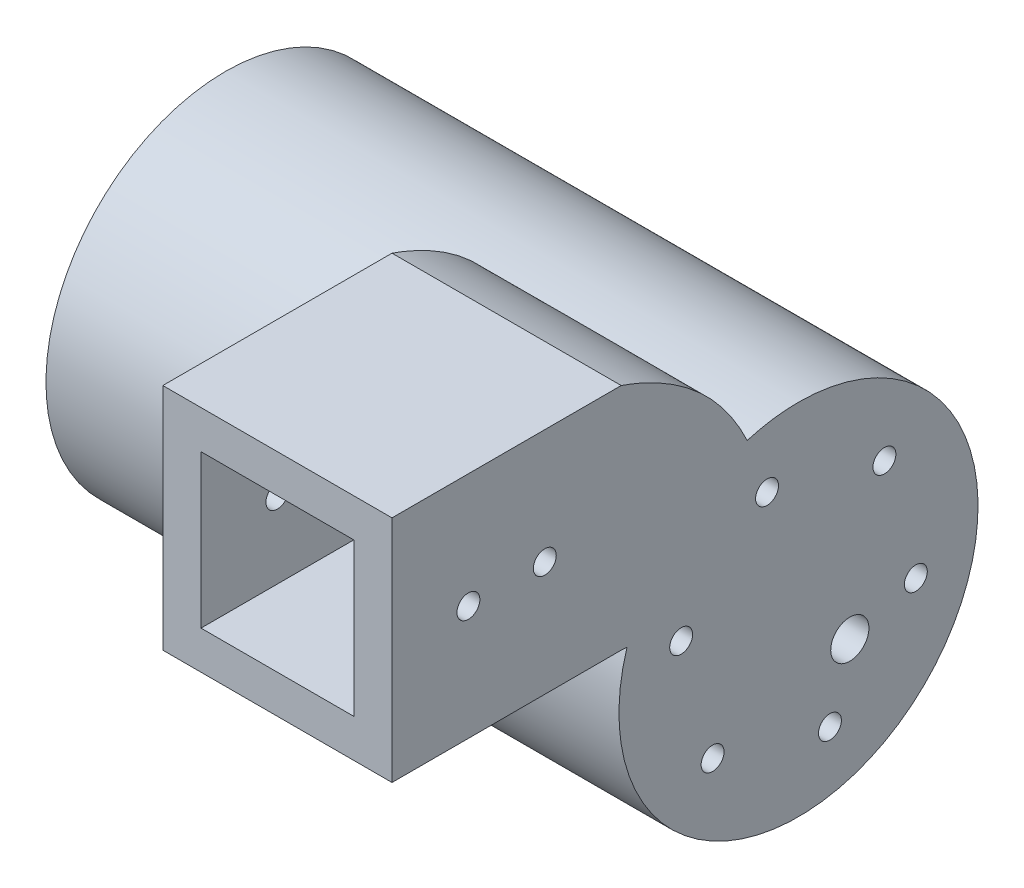
SolidWorks part; units mm, degrees
ref_plane "Front Plane" through (0, 0, 0) normal (0, 0, 1) x (1, 0, 0)
ref_plane "Top Plane" through (0, 0, 0) normal (0, 1, 0) x (1, 0, 0)
ref_plane "Right Plane" through (0, 0, 0) normal (1, 0, 0) x (0, 0, -1)
sketch "Sketch1" plane through (0, 0, 0) normal (0, 0, 1) x (1, 0, 0)
  line L15 (-10, 10) -> (10, 10)
  line L34 (-10, 10) -> (-10, -10)
  line L35 (-10, -10) -> (10, -10)
  line L50 (10, 10) -> (10, -10)
  line L51 (-10, 10) -> (10, -10) construction
  line L66 (-10, -10) -> (10, 10) construction
  line L69 (-15, 15) -> (15, 15)
  line L70 (-15, 15) -> (-15, -15)
  line L71 (-15, -15) -> (15, -15)
  line L72 (15, 15) -> (15, -15)
  point P1 (0, 0)
  dimension "D2" = 20
  dimension "D3" = 20
  dimension "D13" = 30
extrude "Boss-Extrude1" add sketch "Sketch1" along normal blind 30
sketch "Sketch13" plane through (0, 0, 30) normal (0, 0, 1) x (1, 0, 0)
  line L1 (15, 15) -> (-15, 15)
  line L2 (15, 15) -> (15, -15)
  line L3 (15, -15) -> (-15, -15)
  line L4 (-15, 15) -> (-15, -15)
sketch "Sketch21" plane through (15, 0, 0) normal (1, 0, 0) x (0, 0, -1)
  line L0 (0, 15) -> (0, -15) construction
  circle A0 centre (-10, 0) radius 1.5
  circle A1 centre (-20, 0) radius 1.5
  dimension "D1" = 3
  dimension "D3" = 3
  dimension "D2" = 10
  dimension "D4" = 10
extrude "Cut-Extrude1" cut sketch "Sketch21" against normal through all
sketch "Sketch22" plane through (0, 0, 0) normal (0, 0, -1) x (-1, 0, 0)
  line L1 (-15, 15) -> (15, 15)
  line L2 (-15, 15) -> (-15, -15)
  line L3 (-15, -15) -> (15, -15)
  line L4 (15, 15) -> (15, -15)
  line L5 (-15, 15) -> (15, -15) construction
  line L6 (-15, -15) -> (15, 15) construction
  point P0 (0, 0)
extrude "Boss-Extrude2" add sketch "Sketch22" against normal blind 5
sketch "Sketch25" plane through (0, 0, 0) normal (1, 0, 0) x (0, 0, -1)
  line L0 (0, -15) -> (0, -20) construction
  line L1 (0, -20) -> (3.5355, -16.4645) construction
  line L3 (0, 15) -> (0, -15)
  line L5 (3.5355, -16.4645) -> (22.8522, -35.7811)
  line L6 (17.6777, -2.3223) -> (36.9943, -21.639)
  line L7 (22.8522, -35.7811) -> (36.9943, -21.639)
  arc A0 (0, -15) -> (3.5355, -16.4645) centre (0, -20) cw
  spline S0 degree 2 poles (0, 15) (13.0712, 10.4534) (17.6777, -2.3223) knots 0 0 0 1 1 1
  dimension "D1" = 5
  dimension "D2" = 45
  dimension "D3" = 25
  dimension "D5" = 41.46
extrude "Boss-Extrude4" add sketch "Sketch25" along normal mid plane 30
sketch "Sketch26" plane through (15, 0, 0) normal (1, 0, 0) x (0, 0, -1)
  line L0 (29.9232, -28.71) -> (23.2057, -21.9925) construction
  line L1 (22.8522, -35.7811) -> (36.9943, -21.639) construction
  circle A0 centre (23.2057, -21.9925) radius 23.5
  dimension "D2" = 47
  dimension "D1" = 9.5
extrude "Boss-Extrude5" add sketch "Sketch26" against normal blind 75
sketch "Sketch27" plane through (15, 0, 0) normal (1, 0, 0) x (0, 0, -1)
  circle A0 centre (23.2057, -21.9925) radius 18.9
  arc A1 (0.7525, -15.057) -> (16.4959, 0.5292) centre (23.2057, -21.9925) ccw construction
  dimension "D1" = 37.8
extrude "Cut-Extrude2" cut sketch "Sketch27" against normal through all
sketch "Sketch28" plane through (15, 0, 0) normal (1, 0, 0) x (0, 0, -1)
  circle A0 centre (23.2057, -21.9925) radius 18.9
  circle A1 centre (23.2057, -21.9925) radius 18.9 construction
extrude "Boss-Extrude6" add sketch "Sketch28" against normal blind 5
sketch "Sketch29" plane through (15, 0, 0) normal (1, 0, 0) x (0, 0, -1)
  line L0 (-0.2943, -21.9925) -> (46.7057, -21.9925) construction
  line L1 (23.2057, -21.9925) -> (39.8227, -5.3755) construction
  line L2 (23.2057, -21.9925) -> (37.9255, -36.7123) construction
  circle A0 centre (34.4487, -10.7495) radius 1.5
  arc A1 (0.7525, -15.057) -> (16.4959, 0.5292) centre (23.2057, -21.9925) ccw construction
  circle A2 centre (38.564, -26.1078) radius 1.5
  circle A3 centre (27.321, -37.3508) radius 1.5
  circle A4 centre (11.9627, -33.2355) radius 1.5
  circle A5 centre (7.8475, -17.8773) radius 1.5
  circle A6 centre (19.0905, -6.6343) radius 1.5
  circle A7 centre (29.9232, -28.71) radius 2.5
  dimension "D1" = 3
  dimension "D6" = 5
  dimension "D2" = 45
  dimension "D3" = 15.9
  dimension "D5" = 45
  dimension "D7" = 9.5
  dimension "D4" = 6
extrude "Cut-Extrude3" cut sketch "Sketch29" against normal blind 8
sketch "Sketch30" plane through (0, 0, 30) normal (0, 0, 1) x (1, 0, 0)
